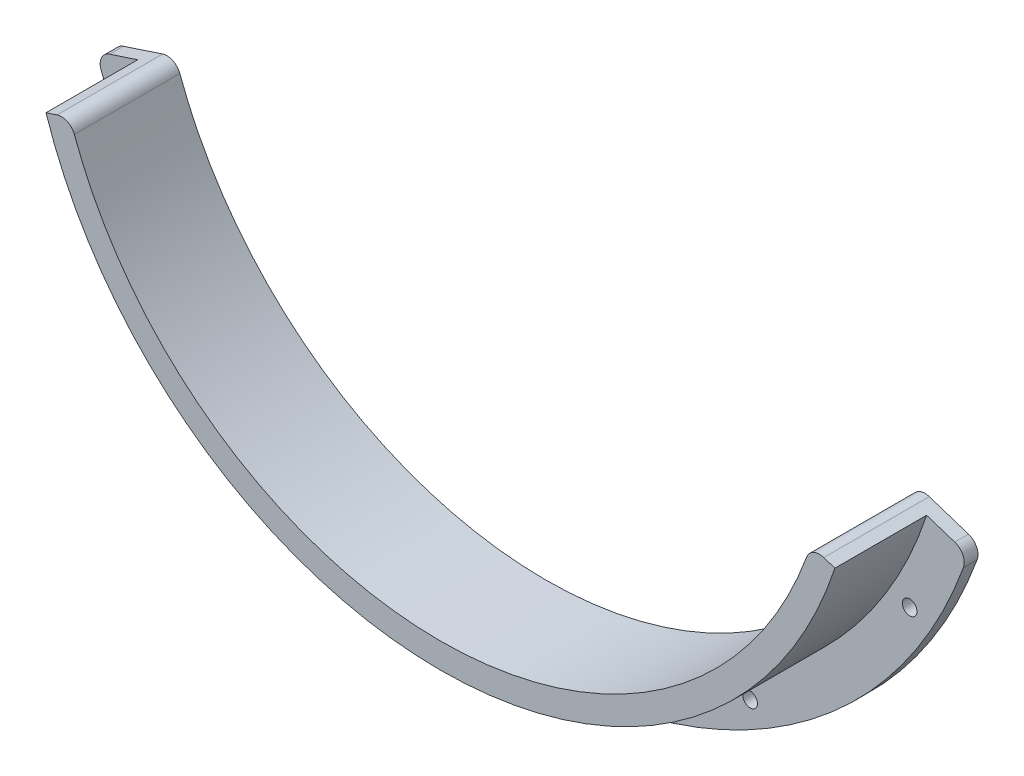
SolidWorks part; units mm, degrees
material "ABS"
ref_plane "前视基准面" through (0, 0, 0) normal (0, 0, 1) x (1, 0, 0)
ref_plane "上视基准面" through (0, 0, 0) normal (0, 1, 0) x (1, 0, 0)
ref_plane "右视基准面" through (0, 0, 0) normal (1, 0, 0) x (0, 0, -1)
other "Configuration Table"
sketch "草图1" plane through (0, 0, 0) normal (0, 0, 1) x (1, 0, 0)
  line L0 (0, 0) -> (0, 95) construction
  line L1 (0, 0) -> (-95, -31.225)
  line L2 (0, 0) -> (95, -31.225)
  circle A0 centre (0, 0) radius 95 construction
  circle A1 centre (0, 0) radius 100
  circle A2 centre (0, 95) radius 1.6
  circle A3 centre (47.5, 82.2724) radius 1.6
  circle A4 centre (82.2724, 47.5) radius 1.6
  circle A5 centre (95, 0) radius 1.6
  circle A6 centre (82.2724, -47.5) radius 1.6
  circle A7 centre (47.5, -82.2724) radius 1.6
  circle A8 centre (0, -95) radius 1.6
  circle A9 centre (-47.5, -82.2724) radius 1.6
  circle A10 centre (-82.2724, -47.5) radius 1.6
  circle A11 centre (-95, 0) radius 1.6
  circle A12 centre (-82.2724, 47.5) radius 1.6
  circle A13 centre (-47.5, 82.2724) radius 1.6
  circle A14 centre (0, 0) radius 85
  dimension "D1" = 200
  dimension "D2" = 190
  dimension "D3" = 3.2
  dimension "D6" = 170
  dimension "D5" = 95
  dimension "D4" = 12
extrude "凸台-拉伸1" add sketch "草图1" along normal blind 3 contours L1 A1 L2 A10 A9 A8 A7 A6
sketch "草图2" plane through (0, 0, 3) normal (0, 0, 1) x (1, 0, 0)
  line L2 (-80.75, -26.5412) -> (-95, -31.225)
  line L3 (95, -31.225) -> (80.75, -26.5412)
  line L4 (-80.75, -26.5412) -> (-95, -31.225)
  line L5 (95, -31.225) -> (80.75, -26.5412)
  circle A0 centre (0, 0) radius 90.5
  arc A3 (-80.75, -26.5412) -> (80.75, -26.5412) centre (0, 0) ccw
  arc A4 (-95, -31.225) -> (95, -31.225) centre (0, 0) ccw
  arc A5 (-80.75, -26.5412) -> (80.75, -26.5412) centre (0, 0) ccw
  arc A6 (-95, -31.225) -> (95, -31.225) centre (0, 0) ccw
  arc M5 (80.75, -26.5412) -> (-80.75, -26.5412) centre (0, 0) cw
  line M6 (-80.75, -26.5412) -> (-95, -31.225)
  dimension "D1" = 181
  dimension "D2" = 0
extrude "凸台-拉伸2" add sketch "草图2" along normal blind 20 contours A0 L5 M6 M5
fillet "圆角1" radius 3 4 edges at (95, -31.225, 1.5) (80.75, -26.5412, 11.5) (-80.75, -26.5412, 11.5) (-95, -31.225, 1.5)
